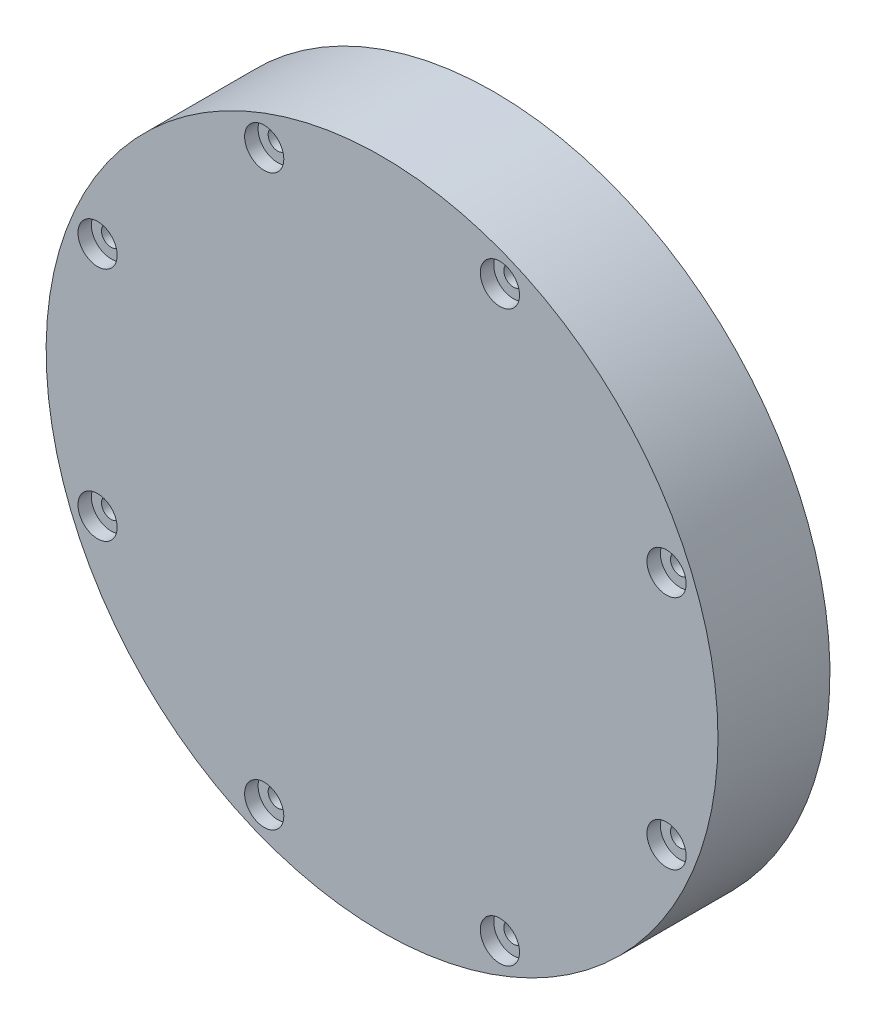
SolidWorks part; units mm, degrees
material "ABS"
ref_plane "Front" through (0, 0, 0) normal (0, 0, 1) x (1, 0, 0)
ref_plane "Top" through (0, 0, 0) normal (0, 1, 0) x (1, 0, 0)
ref_plane "Right" through (0, 0, 0) normal (1, 0, 0) x (0, 0, -1)
sketch "Croquis1" plane through (0, 0, 0) normal (0, 0, 1) x (1, 0, 0)
  line L0 (-15, -49.8498) -> (-15, -54.0833)
  line L1 (15, -49.8498) -> (15, -54.0833)
  line L2 (-15, -47.697) -> (15, -47.697) construction
  line L3 (0, -50) -> (0, 50) construction
  arc A0 (18.9474, -56.9298) -> (-18.9474, -56.9298) centre (0, 0) ccw
  arc A1 (16.9811, -47.0281) -> (-16.9811, -47.0281) centre (0, 0) ccw
  arc A2 (15, -54.0833) -> (18.9474, -56.9298) centre (18, -54.0833) ccw
  arc A3 (-15, -54.0833) -> (-18.9474, -56.9298) centre (-18, -54.0833) cw
  arc A4 (15, -49.8498) -> (16.9811, -47.0281) centre (18, -49.8498) cw
  arc A5 (-15, -49.8498) -> (-16.9811, -47.0281) centre (-18, -49.8498) ccw
  point P8 (0, -47.697)
  dimension "D1" = 120
  dimension "D2" = 100
  dimension "D4" = 3
  dimension "D3" = 30
extrude "Saliente-Extruir1" add sketch "Croquis1" along normal blind 15
sketch "Croquis2" plane through (0, 0, 15) normal (0, 0, 1) x (1, 0, 0)
  circle A0 centre (0, 0) radius 60
  dimension "D1" = 120
extrude "Saliente-Extruir2" add sketch "Croquis2" along normal blind 5
hole_wizard "Refrentado para tornillo con cabeza troncocónica de M31" positions "Croquis3" profile "Croquis5" counterbore size "M3" standard "Ansi Metric" end condition up to next
sketch "Croquis3" plane through (0, 0, 20) normal (0, 0, 1) x (1, 0, 0)
  line L1 (-21.0476, -50.8134) -> (21.0476, 50.8134) construction
  line L4 (0, -50) -> (0, 50) construction
  point P4 (21.0476, 50.8134)
  point P18 (50.8134, 21.0476)
  point P19 (50.8134, -21.0476)
  point P20 (21.0476, -50.8134)
  point P21 (-21.0476, -50.8134)
  point P22 (-50.8134, -21.0476)
  point P23 (-50.8134, 21.0476)
  point P24 (-21.0476, 50.8134)
  dimension "D1" = 22.5
  dimension "D2" = 110
  dimension "D3" = 8
sketch "Croquis5" plane through (-21.0476, 50.8134, 20) normal (1, 0, 0) x (0, -1, 0)
  line L0 (0, 0) -> (0, 20)
  line L1 (0, 20) -> (1.7, 20)
  line L3 (1.7, 20) -> (1.7, 2.4)
  line L4 (1.7, 2.4) -> (3.5, 2.4)
  line L5 (3.5, 2.4) -> (3.5, 0)
  line L7 (3.5, 0) -> (0, 0)
  line L11 (0, -6.35) -> (0, 107.95) construction
  dimension "Diámetro de taladro hasta el siguiente" = 3.4
  dimension "Profundidad de taladro hasta el siguiente" = 20
  dimension "Diámetro de refrentado" = 7
  dimension "Profundidad de refrentado" = 2.4
sketch "Croquis6" plane through (0, 0, 0) normal (1, 0, 0) x (0, 0, -1)
  line L0 (40.5, 22.0023) -> (40.5, 0) construction
  line L1 (40.5, 0) -> (62.5023, 0) construction
  line L2 (-20, 60) -> (-20, -60) construction
  point P4 (67.2995, 22.0023)
  dimension "D1" = 60.5
